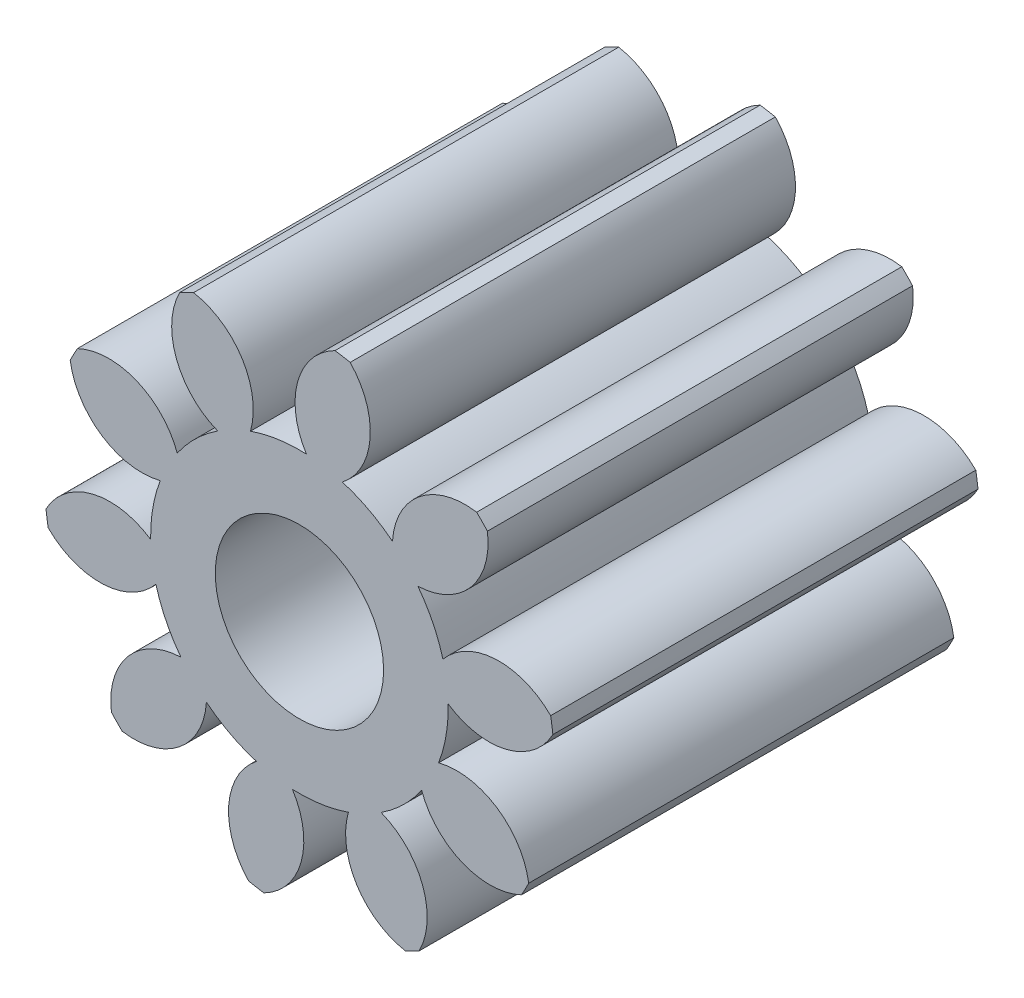
SolidWorks part; units mm, degrees
ref_plane "Alzado" through (0, 0, 0) normal (0, 0, 1) x (1, 0, 0)
ref_plane "Planta" through (0, 0, 0) normal (0, 1, 0) x (1, 0, 0)
ref_plane "Vista lateral" through (0, 0, 0) normal (1, 0, 0) x (0, 0, -1)
sketch "Croquis1" plane through (0, 0, 0) normal (0, 0, 1) x (1, 0, 0)
  circle A0 centre (0, 0) radius 3
  circle A1 centre (0, 0) radius 0.99
  dimension "D1" = 6
  dimension "D2" = 1.98
extrude "Saliente-Extruir1" add sketch "Croquis1" along normal blind 5
sketch "Croquis2" plane through (0, 0, 5) normal (0, 0, 1) x (1, 0, 0)
  line L0 (0, 0) -> (0, 3.4451) construction
  line L1 (0, 0) -> (1.2825, 3.5237) construction
  line L2 (0, 2.5) -> (0.8035, 2.2076) construction
  line L3 (0, 0) -> (-0.5, 3.4451) construction
  circle A0 centre (0, 0) radius 3
  circle A1 centre (0, 0) radius 2.5
  circle A2 centre (0, 0) radius 1.75
  circle A3 centre (0.8035, 2.2076) radius 0.8551
  circle A4 centre (-1.3979, 1.8881) radius 0.8551
  dimension "D1" = 5
  dimension "D2" = 3.5
  dimension "D3" = 20
  dimension "D4" = 0.5
extrude "Cortar-Extruir1" cut sketch "Croquis2" against normal blind 5 contours A1 A4 A2 A3 | A0 A4 A1 A3
pattern_circular "MatrizC1" count 10 over 360 about axis through (0, 0, 0) along (0, 0, 1) of "Cortar-Extruir1"
